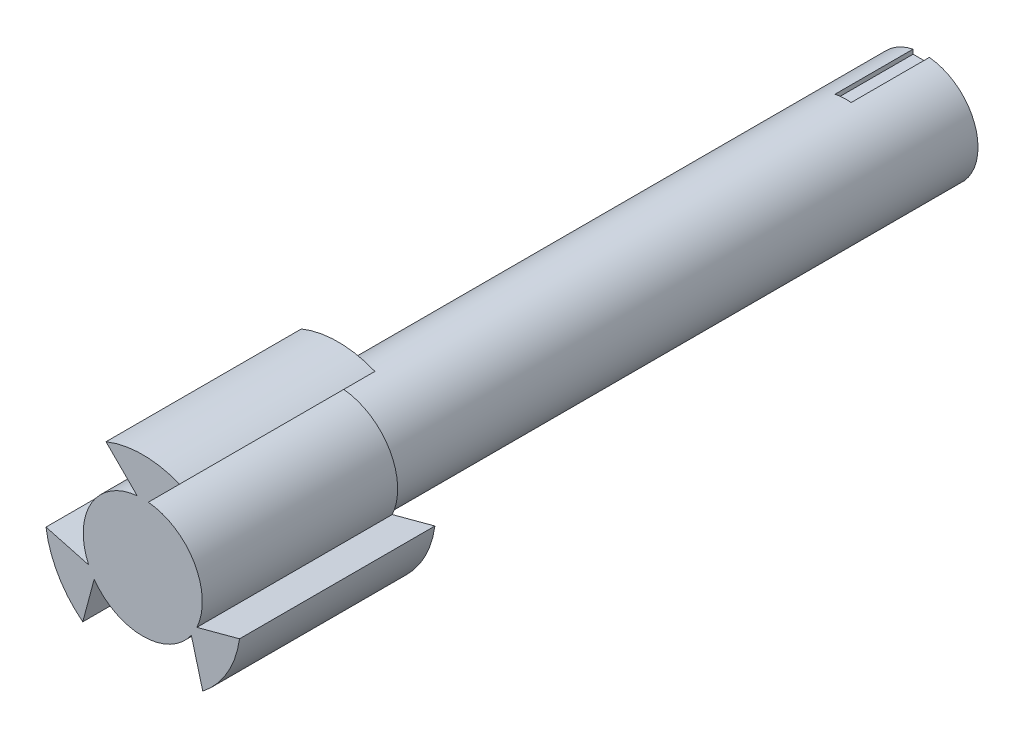
SolidWorks part; units mm, degrees
ref_plane "Front Plane" through (0, 0, 0) normal (0, 0, 1) x (1, 0, 0)
ref_plane "Top Plane" through (0, 0, 0) normal (0, 1, 0) x (1, 0, 0)
ref_plane "Right Plane" through (0, 0, 0) normal (1, 0, 0) x (0, 0, -1)
sketch "Sketch1" plane through (0, 0, 0) normal (0, 0, 1) x (1, 0, 0)
  line L3 (0, 0) -> (0, 100)
  line L4 (-5.6781, 60.6781) -> (-37.6441, 92.6441)
  line L5 (5.6781, 60.6781) -> (37.6441, 92.6441)
  line L6 (49.7097, -35.2565) -> (61.4101, -78.9228)
  line L7 (55.3879, -25.4217) -> (99.0542, -13.7213)
  line L8 (-55.3879, -25.4217) -> (-99.0542, -13.7213)
  line L9 (-49.7097, -35.2565) -> (-61.4101, -78.9228)
  arc A3 (37.6441, 92.6441) -> (-37.6441, 92.6441) centre (0, 0) ccw
  arc A4 (-5.6781, 60.6781) -> (-55.3879, -25.4217) centre (0, 0) ccw
  arc A5 (61.4101, -78.9228) -> (99.0542, -13.7213) centre (0, 0) ccw
  arc A6 (-99.0542, -13.7213) -> (-61.4101, -78.9228) centre (0, 0) ccw
  arc A7 (55.3879, -25.4217) -> (5.6781, 60.6781) centre (0, 0) ccw
  arc A8 (-49.7097, -35.2565) -> (49.7097, -35.2565) centre (0, 0) ccw
  dimension "D4" = 45
  dimension "D5" = 3
  dimension "D2" = 200
  dimension "D3" = 45
extrude "Boss-Extrude1" add sketch "Sketch1" along normal blind 200
sketch "Sketch2" plane through (0, 0, 200) normal (0, 0, 1) x (1, 0, 0)
  circle A0 centre (0, 0) radius 55
  dimension "D1" = 110
extrude "Boss-Extrude2" add sketch "Sketch2" against normal blind 800
sketch "Sketch4" plane through (0, 0, -600) normal (0, 0, -1) x (-1, 0, 0)
  line L1 (-5.1785, 49.271) -> (-5.1785, 61.8901)
  line L2 (-5.1785, 61.8901) -> (11.4331, 61.8901)
  line L5 (-5.1785, 49.271) -> (11.4331, 49.271)
  line L6 (11.4331, 49.271) -> (11.4331, 61.8901)
extrude "Cut-Extrude1" cut sketch "Sketch4" against normal blind 80
scale "Echelle1" bodies to scale 103 scale about centroid uniform scaling yes scale factor 0.47
